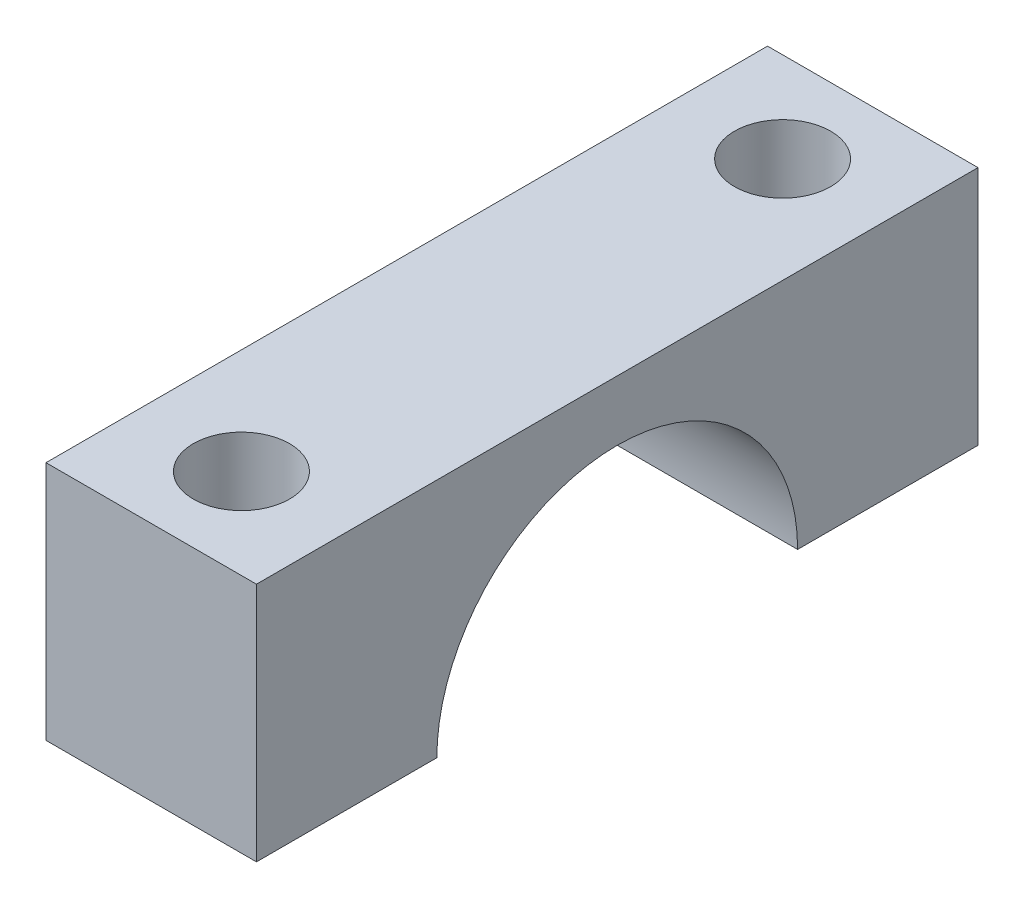
SolidWorks part; units mm, degrees
ref_plane "前视基准面" through (0, 0, 0) normal (0, 0, 1) x (1, 0, 0)
ref_plane "上视基准面" through (0, 0, 0) normal (0, 1, 0) x (1, 0, 0)
ref_plane "右视基准面" through (0, 0, 0) normal (1, 0, 0) x (0, 0, -1)
other "Configuration Table"
sketch "草图1" plane through (0, 0, 0) normal (0, 1, 0) x (1, 0, 0)
  line L1 (0, 0) -> (7, 0)
  line L2 (0, 0) -> (0, -24)
  line L3 (0, -24) -> (7, -24)
  line L4 (7, 0) -> (7, -24)
  dimension "D1" = 7
  dimension "D2" = 24
extrude "凸台-拉伸1" add sketch "草图1" along normal blind 8
sketch "草图2" plane through (0, 0, 0) normal (-1, 0, 0) x (0, 0, 1)
  line L0 (0, 0) -> (24, 0) construction
  circle A0 centre (12, 0) radius 6
  dimension "D1" = 12
extrude "切除-拉伸1" cut sketch "草图2" against normal up to surface (7 mm away) up to face at (7, 4, 12)
sketch "草图3" plane through (0, 0, 0) normal (0, -1, 0) x (1, 0, 0)
  line L0 (3.5, 24) -> (3.5, -1.787) construction
  line L1 (0, 24) -> (7, 24) construction
  line L2 (0, 21) -> (9.6773, 21) construction
  line L3 (0, 18) -> (0, 24) construction
  line L4 (0, 3) -> (10.9829, 3) construction
  line L5 (0, 0) -> (0, 6) construction
  circle A0 centre (3.5, 21) radius 1.6
  circle A1 centre (3.5, 3) radius 1.6
  point P16 (0, 0)
  point P17 (0, 0)
  dimension "D1" = 3.2
extrude "切除-拉伸2" cut sketch "草图3" against normal through all
